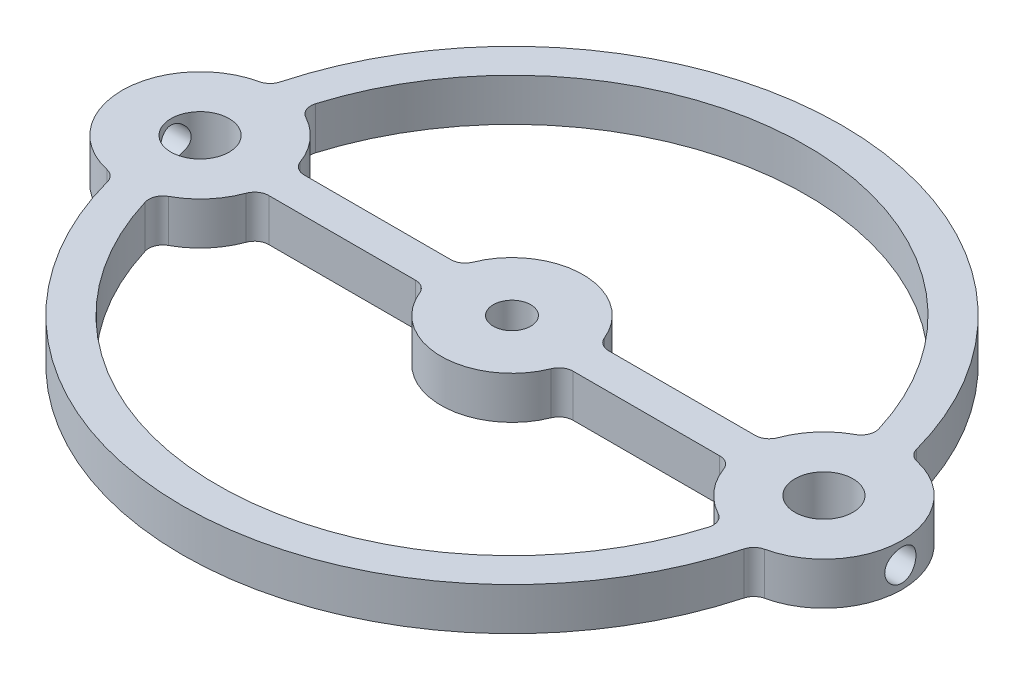
SolidWorks part; units mm, degrees
ref_plane "Front Plane" through (0, 0, 0) normal (0, 0, 1) x (1, 0, 0)
ref_plane "Top Plane" through (0, 0, 0) normal (0, 1, 0) x (1, 0, 0)
ref_plane "Right Plane" through (0, 0, 0) normal (1, 0, 0) x (0, 0, -1)
sketch "Sketch1" plane through (0, 0, 0) normal (0, 1, 0) x (1, 0, 0)
  circle A0 centre (0, 0) radius 12.7
  circle A1 centre (0, 0) radius 3.3528
  dimension "D1" = 25.4
  dimension "D2" = 6.7056
extrude "Boss-Extrude1" add sketch "Sketch1" along normal mid plane 7.62
sketch "Sketch2" plane through (0, 0, 0) normal (0, 1, 0) x (1, 0, 0)
  line L0 (12.2967, 3.175) -> (42.2756, 3.175)
  line L1 (12.2967, -3.175) -> (42.2756, -3.175)
  circle A0 centre (0, 0) radius 12.7 construction
  arc A1 (42.2756, -3.175) -> (42.2756, 3.175) centre (55.88, 0) ccw
  circle A3 centre (55.88, 0) radius 5.207
  arc A4 (12.2967, -3.175) -> (12.2967, 3.175) centre (0, 0) ccw
  dimension "D2" = 13.97
  dimension "D3" = 6.35
  dimension "D1" = 10.414
  dimension "D4" = 55.88
extrude "Boss-Extrude2" add sketch "Sketch2" along normal mid plane 7.62
ref_plane "Plane1" through (69.85, 0, 0) normal (1, 0, 0) x (0, 0, -1)
sketch "Sketch3" plane through (69.85, 0, 0) normal (1, 0, 0) x (0, 0, -1)
  circle A0 centre (0, 0) radius 2.794
  dimension "D1" = 5.588
extrude "Cut-Extrude1" cut sketch "Sketch3" against normal up to next
mirror "Mirror1" about plane through (0, 0, 0) normal (1, 0, 0) of "Cut-Extrude1", "Boss-Extrude2"
sketch "Sketch4" plane through (0, 0, 0) normal (0, 1, 0) x (1, 0, 0)
  circle A0 centre (0, 0) radius 55.88 construction
  arc A1 (-57.3989, -13.8872) -> (57.3989, -13.8872) centre (0, 0) ccw
  arc A2 (-51.0489, -13.1081) -> (51.0489, -13.1081) centre (0, 0) ccw
  arc A3 (42.2756, -3.175) -> (42.2756, 3.175) centre (55.88, 0) ccw construction
  arc A4 (-42.2756, 3.175) -> (-42.2756, -3.175) centre (-55.88, 0) ccw construction
  arc A5 (42.2756, -3.175) -> (42.2756, 3.175) centre (55.88, 0) ccw
  arc A6 (-42.2756, 3.175) -> (-42.2756, -3.175) centre (-55.88, 0) ccw
  arc A7 (51.0489, 13.1081) -> (-51.0489, 13.1081) centre (0, 0) ccw
  circle A8 centre (0, 0) radius 59.055 construction
  circle A9 centre (0, 0) radius 52.705 construction
  arc A10 (57.3989, 13.8872) -> (-57.3989, 13.8872) centre (0, 0) ccw
  point P4 (52.7134, 0.9672)
  point P13 (59.0634, 0.9672)
  dimension "D1" = 3.175
  dimension "D2" = 3.175
extrude "Boss-Extrude3" add sketch "Sketch4" along normal mid plane 7.62 contours A6 A1 A5 A2 | A5 A10 A6 A7
fillet "Fillet1" radius 2.54 16 edges at (12.2967, 0, -3.175) (12.2967, 0, 3.175) (42.2756, 0, -3.175) (42.2756, 0, 3.175) (57.3989, 0, -13.8872) (57.3989, 0, 13.8872) (51.0489, 0, -13.1081) (51.0489, 0, 13.1081) (-57.3989, 0, -13.8872) (-57.3989, 0, 13.8872) (-51.0489, 0, 13.1081) (-42.2756, 0, -3.175) (-42.2756, 0, 3.175) (-51.0489, 0, -13.1081) (-12.2967, 0, -3.175) (-12.2967, 0, 3.175)
